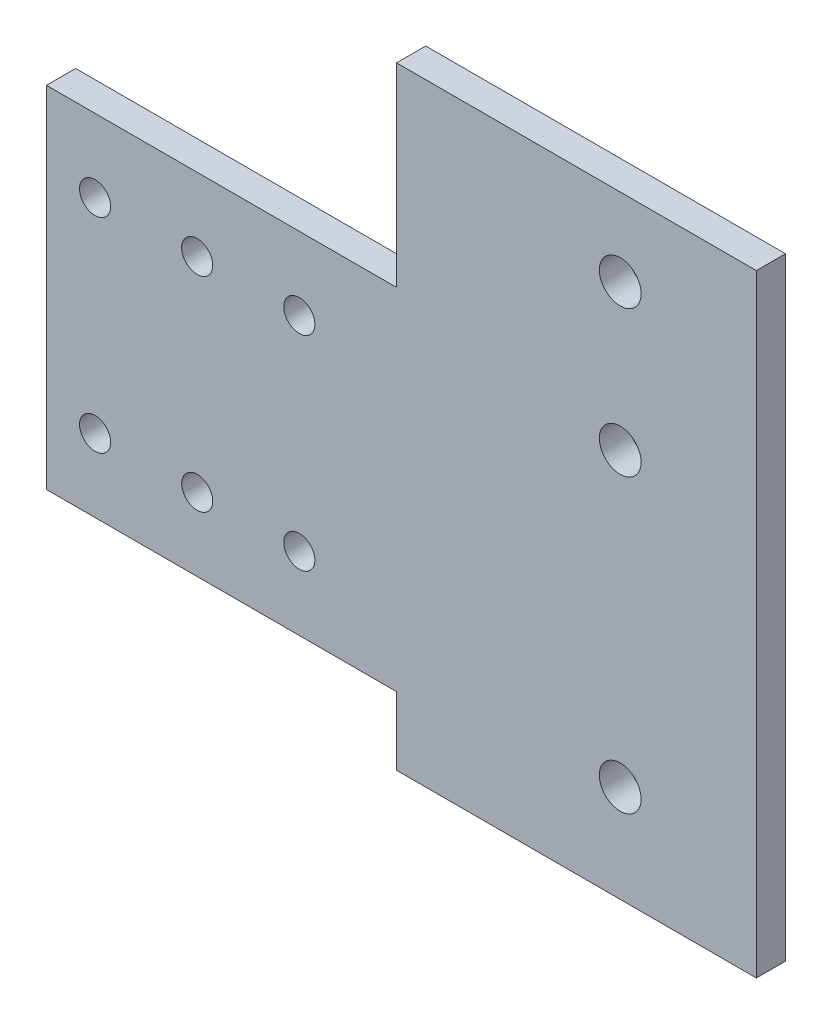
SolidWorks part; units mm, degrees
material "Thornel VCB-20 碳布"
ref_plane "前视基准面" through (0, 0, 0) normal (0, 0, 1) x (1, 0, 0)
ref_plane "上视基准面" through (0, 0, 0) normal (0, 1, 0) x (1, 0, 0)
ref_plane "右视基准面" through (0, 0, 0) normal (1, 0, 0) x (0, 0, -1)
other "Configuration Table"
sketch "草图1" plane through (0, 0, 0) normal (0, 0, 1) x (1, 0, 0)
  line L0 (0, 0) -> (36, 0)
  line L1 (36, 0) -> (36, 20)
  line L2 (36, 20) -> (73, 20)
  line L3 (73, 20) -> (73, -56)
  line L4 (73, -56) -> (36, -56)
  line L5 (36, -56) -> (36, -36)
  line L6 (36, -36) -> (0, -36)
  line L7 (0, -36) -> (0, 0)
  dimension "D1" = 36
  dimension "D2" = 36
  dimension "D3" = 20
  dimension "D4" = 37
extrude "凸台-拉伸1" add sketch "草图1" along normal blind 3
sketch "草图2" plane through (0, 0, 0) normal (0, 0, -1) x (-1, 0, 0)
  line L0 (-36, 0) -> (0, 0) construction
  line L1 (-26, -7.5) -> (-5, -7.5) construction
  line L2 (-26, -7.5) -> (-26, -28.5) construction
  line L3 (-26, -28.5) -> (-5, -28.5) construction
  line L4 (-5, -7.5) -> (-5, -28.5) construction
  line L5 (0, -36) -> (-36, -36) construction
  line L6 (0, 0) -> (0, -36) construction
  line L7 (-36, -36) -> (-36, -56) construction
  circle A0 centre (-26, -7.5) radius 1.6
  circle A1 centre (-26, -28.5) radius 1.6
  circle A2 centre (-5, -7.5) radius 1.6
  circle A3 centre (-5, -28.5) radius 1.6
  circle A4 centre (-15.5, -28.5) radius 1.6
  circle A5 centre (-15.5, -7.5) radius 1.6
  dimension "D5" = 3.2
  dimension "D1" = 7.5
  dimension "D2" = 7.5
  dimension "D3" = 5
  dimension "D4" = 10
extrude "切除-拉伸1" cut sketch "草图2" against normal through all
sketch "草图3" plane through (0, 0, 0) normal (0, 0, -1) x (-1, 0, 0)
  circle A0 centre (-59, -33) radius 2.15
  circle A1 centre (-59, -33) radius 2.5
  circle A2 centre (-59, -33) radius 2.5 construction
  circle A3 centre (-59, -48) radius 2.5
  circle A4 centre (-59, -48) radius 2.5 construction
  circle A5 centre (-59, -48) radius 2.15
  dimension "D3" = 4.3
  dimension "D1" = 0
  dimension "D2" = 0
extrude "切除-拉伸2" cut sketch "草图3" against normal through all
sketch "草图4" plane through (0, 0, 0) normal (0, 0, -1) x (-1, 0, 0)
  circle A0 centre (-59, -3) radius 2.5 construction
  circle A1 centre (-59, -3) radius 2.5 construction
  circle A2 centre (-59, 12) radius 2.5 construction
  circle A3 centre (-59, 12) radius 2.5 construction
  circle A4 centre (-59, 12) radius 2.15
  circle A5 centre (-59, -3) radius 2.15
  dimension "D1" = 4.3
extrude "切除-拉伸3" cut sketch "草图4" against normal through all
sketch "草图5" plane through (0, 0, 3) normal (0, 0, 1) x (1, 0, 0)
  line L0 (36, -43) -> (73, -43)
  line L1 (36, -43) -> (36, -56)
  line L2 (73, -56) -> (73, -43)
  line L8 (0, 0) -> (0, -36)
  line L9 (0, -36) -> (36, -36)
  line L10 (36, -36) -> (36, -56)
  line L11 (36, -56) -> (73, -56)
  line L12 (73, -56) -> (73, 20)
  line L13 (73, 20) -> (36, 20)
  line L14 (36, 20) -> (36, 0)
  line L15 (36, 0) -> (0, 0)
  line L16 (0, 0) -> (0, -36) construction
  line L17 (0, -36) -> (36, -36) construction
  line L18 (36, -36) -> (36, -56) construction
  line L19 (36, -56) -> (73, -56)
  line L20 (73, -56) -> (73, 20) construction
  line L21 (73, 20) -> (36, 20) construction
  line L22 (36, 20) -> (36, 0) construction
  line L23 (36, 0) -> (0, 0) construction
  dimension "D2" = 13
  dimension "D1" = 0
extrude "切除-拉伸4" cut sketch "草图5" against normal through all
